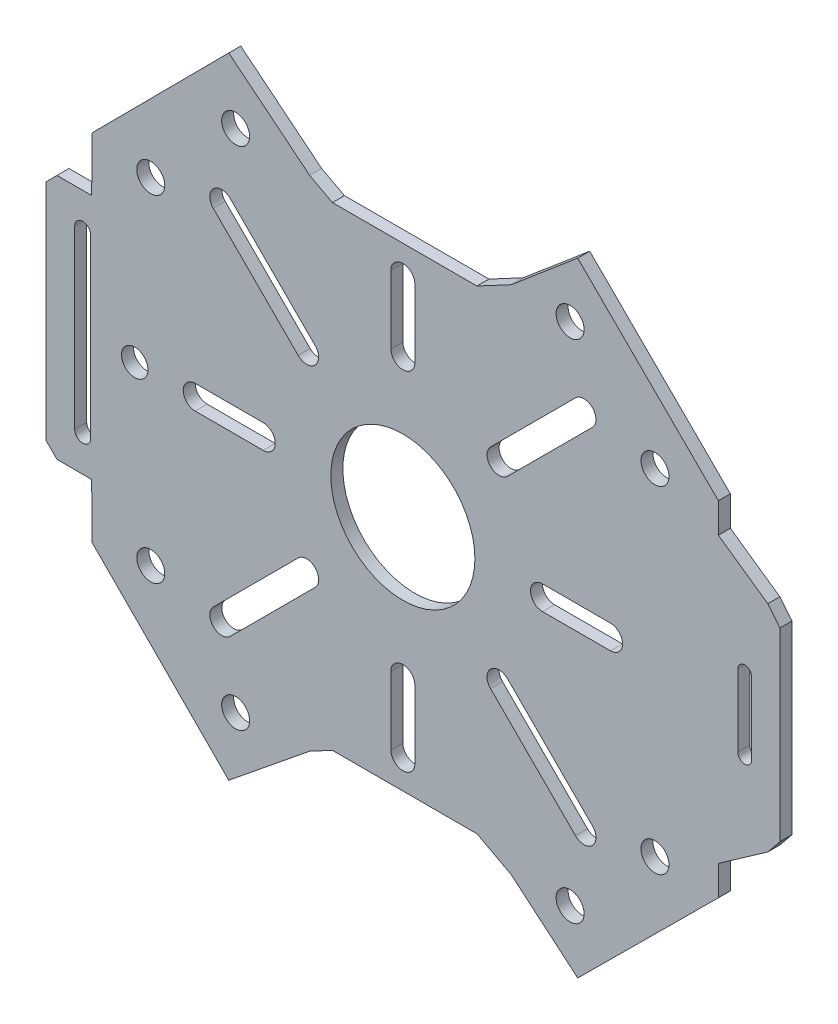
SolidWorks part; units mm, degrees
ref_plane "前视基准面" through (0, 0, 0) normal (0, 0, 1) x (1, 0, 0)
ref_plane "上视基准面" through (0, 0, 0) normal (0, 1, 0) x (1, 0, 0)
ref_plane "右视基准面" through (0, 0, 0) normal (1, 0, 0) x (0, 0, -1)
sketch "Upper_board" plane through (0, 0, 0) normal (0, 0, 1) x (1, 0, 0)
  line L0 (146.4713, -65.3649) -> (146.4713, 899.9684) construction
  line L1 (-20.8934, 31.6066) -> (-31.5, 21) construction
  line L2 (0, 0) -> (0, 48.26) construction
  line L3 (0, 0) -> (79.7901, 0) construction
  line L4 (0, 29.6377) -> (9.2582, 29.6377)
  line L5 (9.2582, 29.6377) -> (13.5301, 31.9144)
  line L6 (13.5301, 31.9144) -> (21.8452, 38.9473)
  line L7 (21.8452, 38.9473) -> (39.4221, 21.4832)
  line L8 (39.4221, 21.4832) -> (39.4221, 17.7594)
  line L9 (39.4221, 17.7594) -> (45.6027, 13.4317)
  line L10 (45.6027, 13.4317) -> (47.1171, 11.5642)
  line L11 (47.1171, 11.5642) -> (47.1171, -11.5642)
  line L12 (45.6027, -13.4317) -> (47.1171, -11.5642)
  line L13 (39.4221, -17.7594) -> (45.6027, -13.4317)
  line L14 (39.4221, -21.4832) -> (39.4221, -17.7594)
  line L15 (21.8452, -38.9473) -> (39.4221, -21.4832)
  line L16 (13.5301, -31.9144) -> (21.8452, -38.9473)
  line L17 (9.2582, -29.6377) -> (13.5301, -31.9144)
  line L18 (0, -29.6377) -> (9.2582, -29.6377)
  line L19 (0, 29.6377) -> (-8.8004, 29.6377)
  line L20 (-8.8004, 29.6377) -> (-11.6488, 31.1557)
  line L21 (-11.6488, 31.1557) -> (-21.7549, 39.351)
  line L22 (-21.7549, 39.351) -> (-38.8505, 22.145)
  line L23 (-38.8505, 22.145) -> (-38.8781, 15.3642)
  line L24 (-38.8781, 15.3642) -> (-43.2196, 15.3642)
  line L25 (-43.2196, 15.3642) -> (-44.5853, 13.9896)
  line L26 (-44.5853, 13.9896) -> (-44.5853, -13.9896)
  line L27 (-8.8004, -29.6377) -> (-11.6488, -31.1557)
  line L28 (0, -29.6377) -> (-8.8004, -29.6377)
  line L29 (-11.6488, -31.1557) -> (-21.7549, -39.351)
  line L30 (-21.7549, -39.351) -> (-38.8505, -22.145)
  line L31 (-38.8505, -22.145) -> (-38.8781, -15.3642)
  line L32 (-38.8781, -15.3642) -> (-43.2196, -15.3642)
  line L33 (-43.2196, -15.3642) -> (-44.5853, -13.9896)
  line L34 (-22.627, 22.627) -> (-12.0212, 12.0212) construction
  line L35 (-21.5663, 23.6876) -> (-10.9606, 13.0819)
  line L36 (-23.6876, 21.5663) -> (-13.0819, 10.9606)
  line L37 (0, 17.4457) -> (0, 25.9457) construction
  line L38 (-1.5, 17.4457) -> (-1.5, 25.9457)
  line L39 (1.5, 17.4457) -> (1.5, 25.9457)
  line L40 (0, -17.4457) -> (0, -25.9457) construction
  line L41 (-1.5, -17.4457) -> (-1.5, -25.9457)
  line L42 (1.5, -17.4457) -> (1.5, -25.9457)
  line L43 (0, 0) -> (-17.3241, 17.3241) construction
  line L44 (-17.4457, 0) -> (-25.9457, 0) construction
  line L45 (-17.4457, 1.5) -> (-25.9457, 1.5)
  line L46 (-17.4457, -1.5) -> (-25.9457, -1.5)
  line L47 (17.4457, 0) -> (25.9457, 0) construction
  line L48 (17.4457, 1.5) -> (25.9457, 1.5)
  line L49 (17.4457, -1.5) -> (25.9457, -1.5)
  line L50 (-22.627, -22.627) -> (-12.0212, -12.0212) construction
  line L51 (-21.5663, -23.6876) -> (-10.9606, -13.0819)
  line L52 (-23.6876, -21.5663) -> (-13.0819, -10.9606)
  line L53 (22.627, 22.627) -> (12.0212, 12.0212) construction
  line L54 (21.5663, 23.6876) -> (10.9606, 13.0819)
  line L55 (23.6876, 21.5663) -> (13.0819, 10.9606)
  line L56 (22.627, -22.627) -> (12.0212, -12.0212) construction
  line L57 (21.5663, -23.6876) -> (10.9606, -13.0819)
  line L58 (23.6876, -21.5663) -> (13.0819, -10.9606)
  line L59 (-40, -11) -> (-40, 11) construction
  line L60 (-41, -11) -> (-41, 11)
  line L61 (-39, -11) -> (-39, 11)
  line L62 (42.7214, -4.5) -> (42.7214, 4.5) construction
  line L63 (41.8554, -4.5) -> (41.8554, 4.5)
  line L64 (43.5874, -4.5) -> (43.5874, 4.5)
  circle A0 centre (0, 0) radius 9
  circle A3 centre (-20.8934, 31.6066) radius 1.75
  circle A4 centre (-31.5, 21) radius 1.75
  circle A5 centre (-33.5, 0) radius 1.65
  circle A6 centre (20.8934, 31.6066) radius 1.75
  circle A7 centre (31.5, 21) radius 1.75
  circle A8 centre (-20.8934, -31.6066) radius 1.75
  circle A9 centre (-31.5, -21) radius 1.75
  circle A10 centre (20.8934, -31.6066) radius 1.75
  circle A11 centre (31.5, -21) radius 1.75
  arc A12 (-21.5663, 23.6876) -> (-23.6876, 21.5663) centre (-22.627, 22.627) ccw
  arc A13 (-13.0819, 10.9606) -> (-10.9606, 13.0819) centre (-12.0212, 12.0212) ccw
  arc A14 (-1.5, 17.4457) -> (1.5, 17.4457) centre (0, 17.4457) ccw
  arc A15 (1.5, 25.9457) -> (-1.5, 25.9457) centre (0, 25.9457) ccw
  arc A16 (-1.5, -17.4457) -> (1.5, -17.4457) centre (0, -17.4457) cw
  arc A17 (1.5, -25.9457) -> (-1.5, -25.9457) centre (0, -25.9457) cw
  arc A18 (-17.4457, 1.5) -> (-17.4457, -1.5) centre (-17.4457, 0) cw
  arc A19 (-25.9457, -1.5) -> (-25.9457, 1.5) centre (-25.9457, 0) cw
  arc A20 (17.4457, 1.5) -> (17.4457, -1.5) centre (17.4457, 0) ccw
  arc A21 (25.9457, -1.5) -> (25.9457, 1.5) centre (25.9457, 0) ccw
  arc A22 (-21.5663, -23.6876) -> (-23.6876, -21.5663) centre (-22.627, -22.627) cw
  arc A23 (-13.0819, -10.9606) -> (-10.9606, -13.0819) centre (-12.0212, -12.0212) cw
  arc A24 (21.5663, 23.6876) -> (23.6876, 21.5663) centre (22.627, 22.627) cw
  arc A25 (13.0819, 10.9606) -> (10.9606, 13.0819) centre (12.0212, 12.0212) cw
  arc A26 (21.5663, -23.6876) -> (23.6876, -21.5663) centre (22.627, -22.627) ccw
  arc A27 (13.0819, -10.9606) -> (10.9606, -13.0819) centre (12.0212, -12.0212) ccw
  arc A28 (-41, -11) -> (-39, -11) centre (-40, -11) ccw
  arc A29 (-39, 11) -> (-41, 11) centre (-40, 11) ccw
  arc A30 (41.8554, -4.5) -> (43.5874, -4.5) centre (42.7214, -4.5) ccw
  arc A31 (43.5874, 4.5) -> (41.8554, 4.5) centre (42.7214, 4.5) ccw
  point P37 (47.1171, 0)
  point P52 (-17.3241, 17.3241)
  point P59 (-44.5853, 0)
  point P66 (0, 21.6957)
  point P78 (0, -21.6957)
  point P84 (-21.6957, 0)
  point P91 (21.6957, 0)
  point P98 (-17.3241, -17.3241)
  point P105 (17.3241, 17.3241)
  point P112 (17.3241, -17.3241)
  point P119 (-40, 0)
  point P124 (42.7214, 0)
  point P131 (0, 0)
  point P133 (32.4239, 0)
  dimension "D1" = 21
  dimension "D2" = 31.5
  dimension "D3" = 3.3
  dimension "D6" = 3.5
  dimension "D9" = 45
  dimension "D11" = 0
  dimension "D12" = 40
  dimension "D4" = 33.5
  dimension "D5" = 15
  dimension "D7" = 29.6377
  dimension "D8" = 47.1171
  dimension "D10" = 24.5
  dimension "D13" = 0
  dimension "D14" = 21
  dimension "D15" = 45
extrude "凸台-拉伸1" add sketch "Upper_board" along normal blind 1.5
